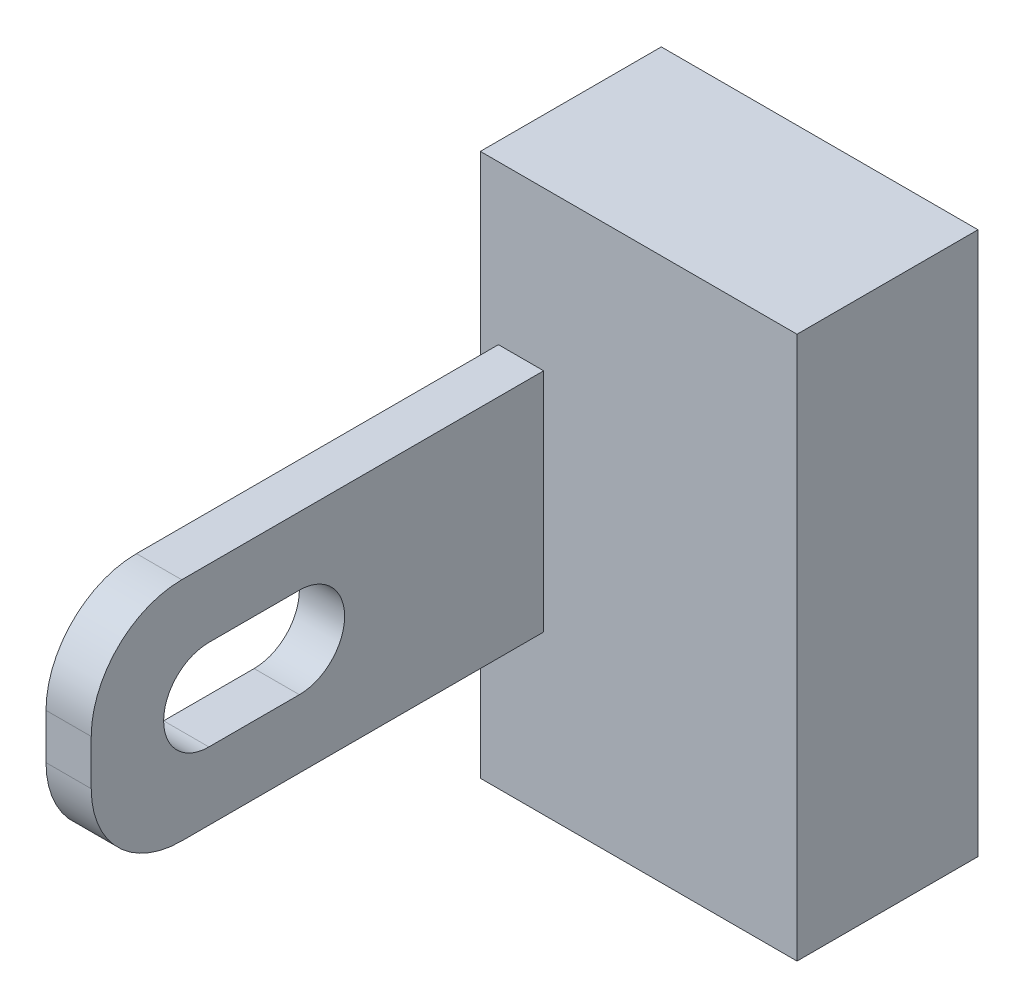
SolidWorks part; units mm, degrees
ref_plane "Front Plane" through (0, 0, 0) normal (0, 0, 1) x (1, 0, 0)
ref_plane "Top Plane" through (0, 0, 0) normal (0, 1, 0) x (1, 0, 0)
ref_plane "Right Plane" through (0, 0, 0) normal (1, 0, 0) x (0, 0, -1)
sketch "Sketch1" plane through (0, 0, 0) normal (0, 0, 1) x (1, 0, 0)
  line L1 (-1.75, 3) -> (1.75, 3)
  line L2 (-1.75, 3) -> (-1.75, -3)
  line L3 (-1.75, -3) -> (1.75, -3)
  line L4 (1.75, 3) -> (1.75, -3)
  line L5 (-1.75, 3) -> (1.75, -3) construction
  line L6 (-1.75, -3) -> (1.75, 3) construction
  point P0 (0, 0)
  dimension "D1" = 6
  dimension "D2" = 3.5
extrude "Boss-Extrude1" add sketch "Sketch1" along normal blind 2
sketch "Sketch2" plane through (0, 0, 2) normal (0, 0, 1) x (1, 0, 0)
  line L0 (0, 0) -> (-2.0759, 0) construction
  line L1 (-1.75, 3) -> (-1.75, -3) construction
  line L2 (-1.55, 1.25) -> (-1.05, 1.25)
  line L3 (-1.55, 1.25) -> (-1.55, -1.25)
  line L4 (-1.55, -1.25) -> (-1.05, -1.25)
  line L5 (-1.05, 1.25) -> (-1.05, -1.25)
  line L6 (-1.55, 1.25) -> (-1.05, -1.25) construction
  line L7 (-1.55, -1.25) -> (-1.05, 1.25) construction
  point P2 (-1.3, 0)
  point P10 (0, 0)
  dimension "D1" = 0.2
  dimension "D2" = 0.5
  dimension "D3" = 2.5
extrude "Boss-Extrude2" add sketch "Sketch2" along normal blind 5
fillet "Fillet1" radius 1 2 edges at (-1.3, -1.25, 7) (-1.3, 1.25, 7)
sketch "Sketch3" plane through (-1.55, 0, 0) normal (-1, 0, 0) x (0, 0, 1)
  line L0 (4.7, 0) -> (5.7, 0) construction
  line L1 (4.7, 0.5) -> (5.7, 0.5)
  line L2 (4.7, -0.5) -> (5.7, -0.5)
  line L3 (7, 0.25) -> (7, -0.25) construction
  arc A0 (4.7, 0.5) -> (4.7, -0.5) centre (4.7, 0) ccw
  arc A1 (5.7, -0.5) -> (5.7, 0.5) centre (5.7, 0) ccw
  point P3 (5.2, 0)
  dimension "D2" = 0.5
  dimension "D1" = 1.3
  dimension "D3" = 1
extrude "Cut-Extrude1" cut sketch "Sketch3" against normal through all
